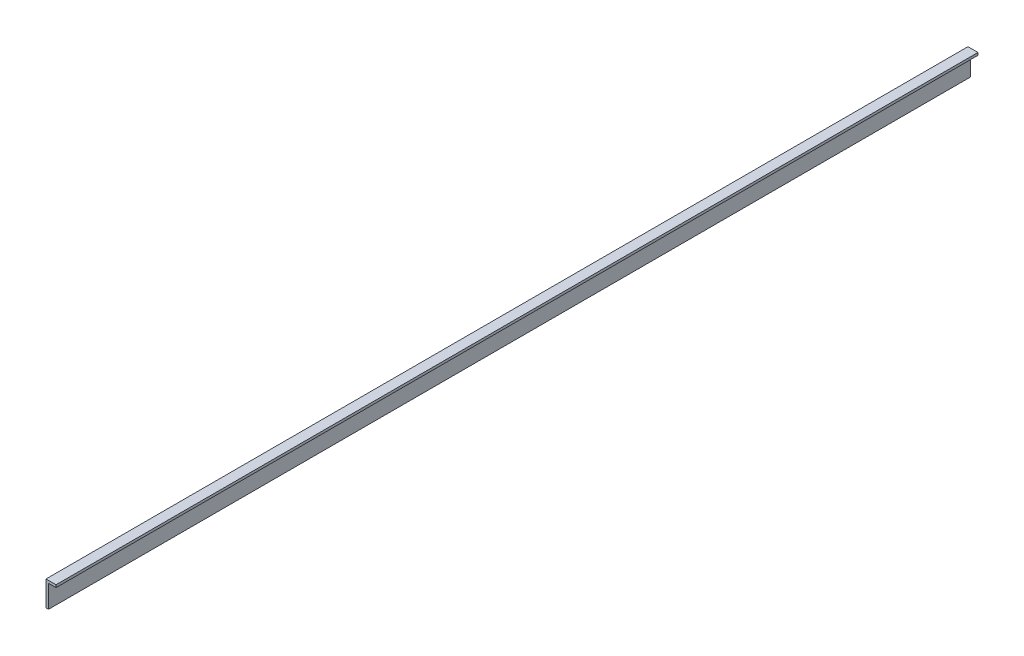
SolidWorks part; units mm, degrees
ref_plane "Front Plane" through (0, 0, 0) normal (0, 0, 1) x (1, 0, 0)
ref_plane "Top Plane" through (0, 0, 0) normal (0, 1, 0) x (1, 0, 0)
ref_plane "Right Plane" through (0, 0, 0) normal (1, 0, 0) x (0, 0, -1)
other "Configuration Table"
sketch "Sketch1" plane through (0, 0, 0) normal (0, 0, 1) x (1, 0, 0)
  line L0 (245.5, 404.5) -> (243.5, 404.5)
  line L1 (243.5, 404.5) -> (243.5, 424.5)
  line L2 (243.5, 424.5) -> (251.5, 424.5)
  line L3 (251.5, 424.5) -> (251.5, 422.5)
  line L4 (251.5, 422.5) -> (245.5, 422.5)
  line L5 (245.5, 422.5) -> (245.5, 404.5)
extrude "STORE_kaset_L_raf_2_sol_1" add sketch "Sketch1" against normal blind 735.5 from offset 20 separate body
